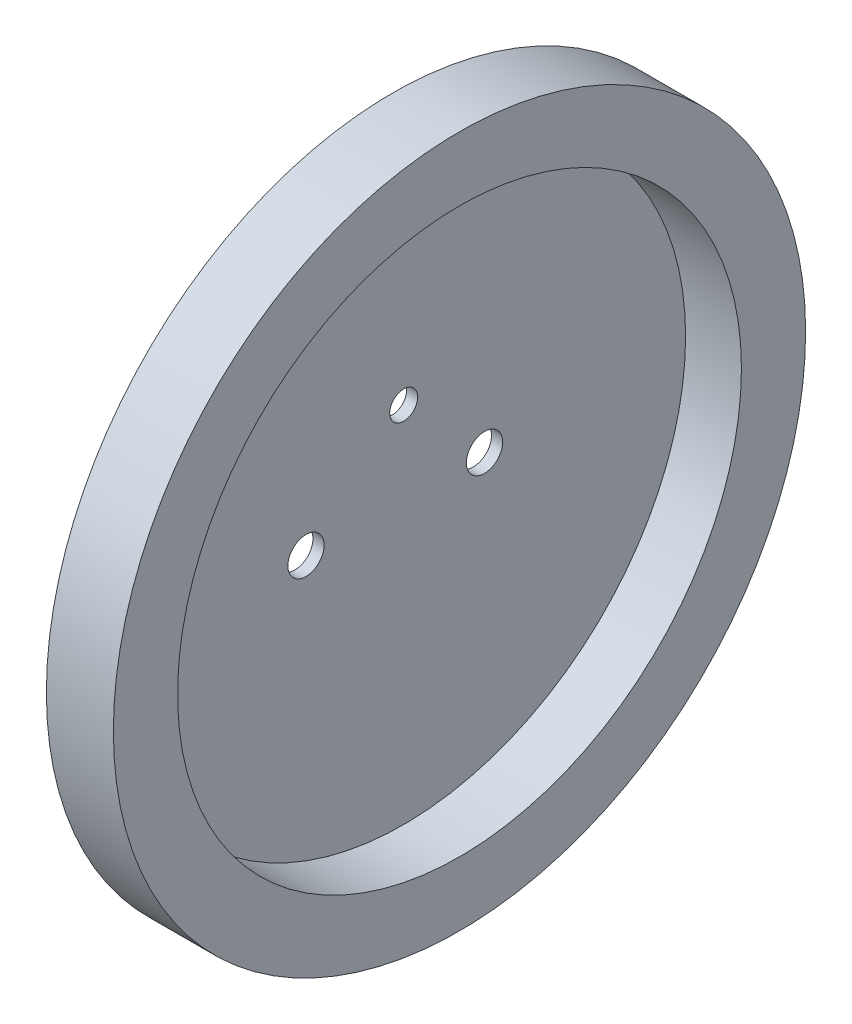
SolidWorks part; units mm, degrees
ref_plane "Front Plane" through (0, 0, 0) normal (0, 0, 1) x (1, 0, 0)
ref_plane "Top Plane" through (0, 0, 0) normal (0, 1, 0) x (1, 0, 0)
ref_plane "Right Plane" through (0, 0, 0) normal (1, 0, 0) x (0, 0, -1)
sketch "Sketch2" plane through (0, 0, 0) normal (1, 0, 0) x (0, 0, -1)
  circle A0 centre (0, 0) radius 62
extrude "Boss-Extrude1" add sketch "Sketch2" along normal blind 12
sketch "Sketch4" plane through (12, 0, 0) normal (1, 0, 0) x (0, 0, -1)
  circle A0 centre (0, 0) radius 50.5
extrude "Cut-Extrude2" cut sketch "Sketch4" against normal blind 10
sketch "Sketch5" plane through (0, 0, 0) normal (-1, 0, 0) x (0, 0, 1)
  line L0 (-62, 0) -> (62, 0) construction
  line L2 (0, 62) -> (0, -62) construction
  circle A0 centre (0, 0) radius 62 construction
  circle A1 centre (0, 14.5815) radius 2.5
  circle A2 centre (-14.481, 0) radius 3.25
  circle A3 centre (17.4978, 0) radius 3.25
extrude "Cut-Extrude3" cut sketch "Sketch5" against normal blind 5
